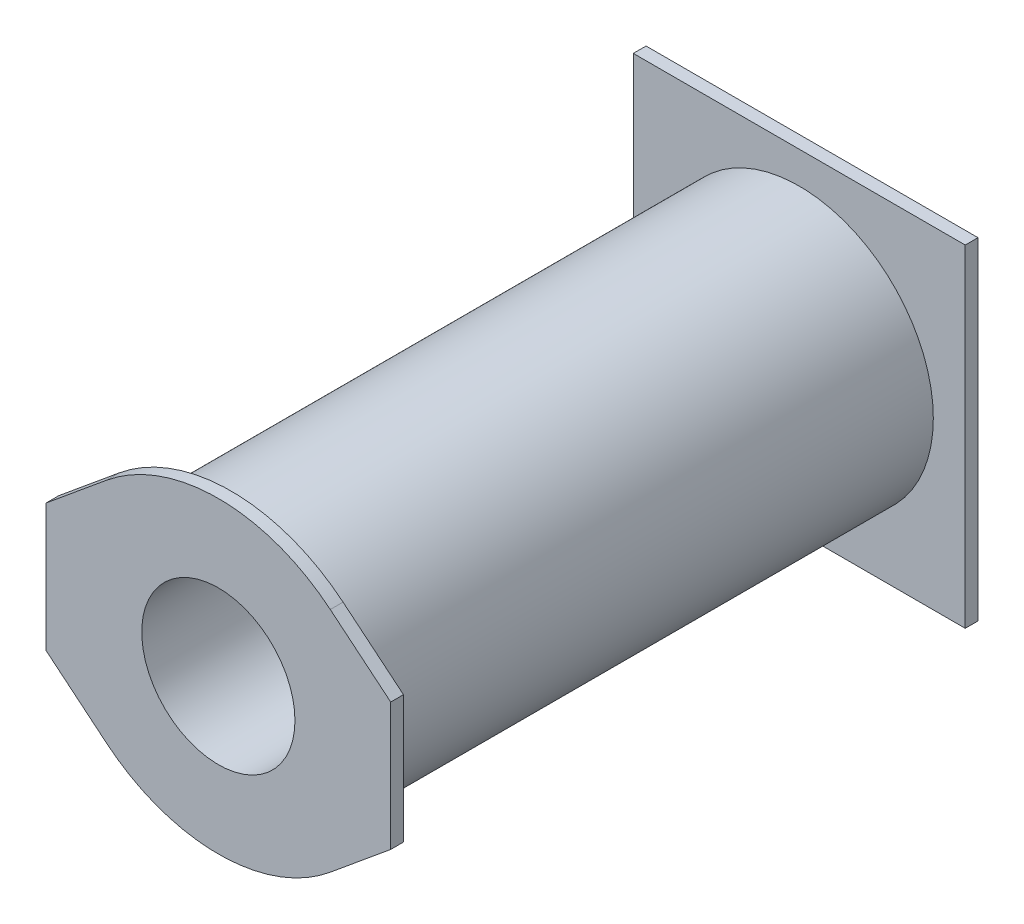
SolidWorks part; units mm, degrees
ref_plane "Alzado" through (0, 0, 0) normal (0, 0, 1) x (1, 0, 0)
ref_plane "Planta" through (0, 0, 0) normal (0, 1, 0) x (1, 0, 0)
ref_plane "Vista lateral" through (0, 0, 0) normal (1, 0, 0) x (0, 0, -1)
sketch "Croquis1" plane through (0, 0, 0) normal (0, 0, 1) x (1, 0, 0)
  line L1 (13, -13) -> (-13, -13)
  line L2 (13, -13) -> (13, 13)
  line L3 (13, 13) -> (-13, 13)
  line L4 (-13, -13) -> (-13, 13)
  line L5 (13, -13) -> (-13, 13) construction
  line L6 (13, 13) -> (-13, -13) construction
  point P0 (0, 0)
  dimension "D1" = 26
extrude "Saliente-Extruir1" add sketch "Croquis1" along normal blind 1
sketch "Croquis2" plane through (0, 0, 1) normal (0, 0, 1) x (1, 0, 0)
  circle A0 centre (0, 0) radius 10.5
  dimension "D1" = 21
extrude "Saliente-Extruir2" add sketch "Croquis2" along normal blind 44.5
sketch "Croquis3" plane through (0, 0, 45.5) normal (0, 0, 1) x (1, 0, 0)
  line L0 (0, 0) -> (-13.5, 0)
  line L1 (-13.5, 0) -> (13.5, 0)
  line L2 (13.5, -5) -> (13.5, 5)
  line L3 (-13.5, -5) -> (-13.5, 5)
  line L4 (-13.5, 5) -> (-8.7669, 8.9102)
  line L5 (-13.5, -5) -> (-8.7669, -8.9102)
  line L6 (13.5, -5) -> (8.7669, -8.9102)
  line L7 (13.5, 5) -> (8.7669, 8.9102)
  arc A1 (-8.7669, 8.9102) -> (8.7669, 8.9102) centre (0, -1.7018) cw
  arc A2 (8.7669, -8.9102) -> (-8.7669, -8.9102) centre (0, 1.7018) cw
  point P8 (13.5, 0)
  point P11 (-13.5, 0)
  circle M2 centre (0, 0) radius 10.5
  dimension "D2" = 13.5
  dimension "D3" = 27
  dimension "D4" = 5
  dimension "D5" = 5
extrude "Saliente-Extruir3" add sketch "Croquis3" along normal blind 1 contours A2 L6 L2 L1 L0 L3 L5 M2 | A1 L4 L3 L0 L1 L2 L7 M2 | L0 L1 M2 | L1 L0 M2
sketch "Croquis4" plane through (0, 0, 46.5) normal (0, 0, 1) x (1, 0, 0)
  circle A0 centre (0, 0) radius 6
  dimension "D1" = 12
extrude "Cortar-Extruir1" cut sketch "Croquis4" against normal through all
